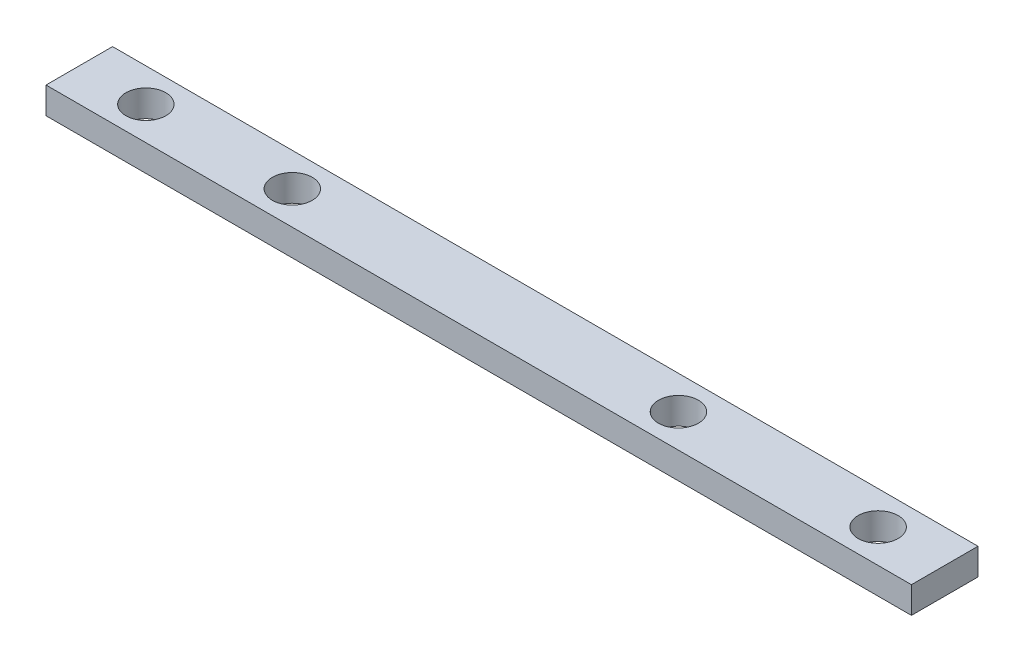
SolidWorks part; units mm, degrees
ref_plane "前视基准面" through (0, 0, 0) normal (0, 0, 1) x (1, 0, 0)
ref_plane "上视基准面" through (0, 0, 0) normal (0, 1, 0) x (1, 0, 0)
ref_plane "右视基准面" through (0, 0, 0) normal (1, 0, 0) x (0, 0, -1)
other "Configuration Table"
sketch "草图1" plane through (0, 0, 0) normal (0, 1, 0) x (1, 0, 0)
  line L1 (0, -5) -> (65, -5)
  line L2 (0, -5) -> (0, 0)
  line L3 (0, 0) -> (65, 0)
  line L4 (65, -5) -> (65, 0)
  circle A2 centre (5, -2.5) radius 1.5
  circle A3 centre (16, -2.5) radius 1.5
  circle A4 centre (45, -2.5) radius 1.5
  circle A5 centre (60, -2.5) radius 1.5
  point P8 (43, -2.5)
  point P9 (0, -2.5)
  point P14 (0, 0)
  point P15 (0, 0)
  point P16 (58, -2.5)
  point P17 (0, 0)
  point P18 (16, -2.5)
  point P19 (45, -2.5)
  point P20 (60, -2.5)
  dimension "D1" = 3
  dimension "D2" = 5
  dimension "D3" = 5
  dimension "D4" = 5
extrude "凸台-拉伸1" add sketch "草图1" along normal blind 2 contours L3 L4 L1 L2 | A2 | A3 | A4 | A5
